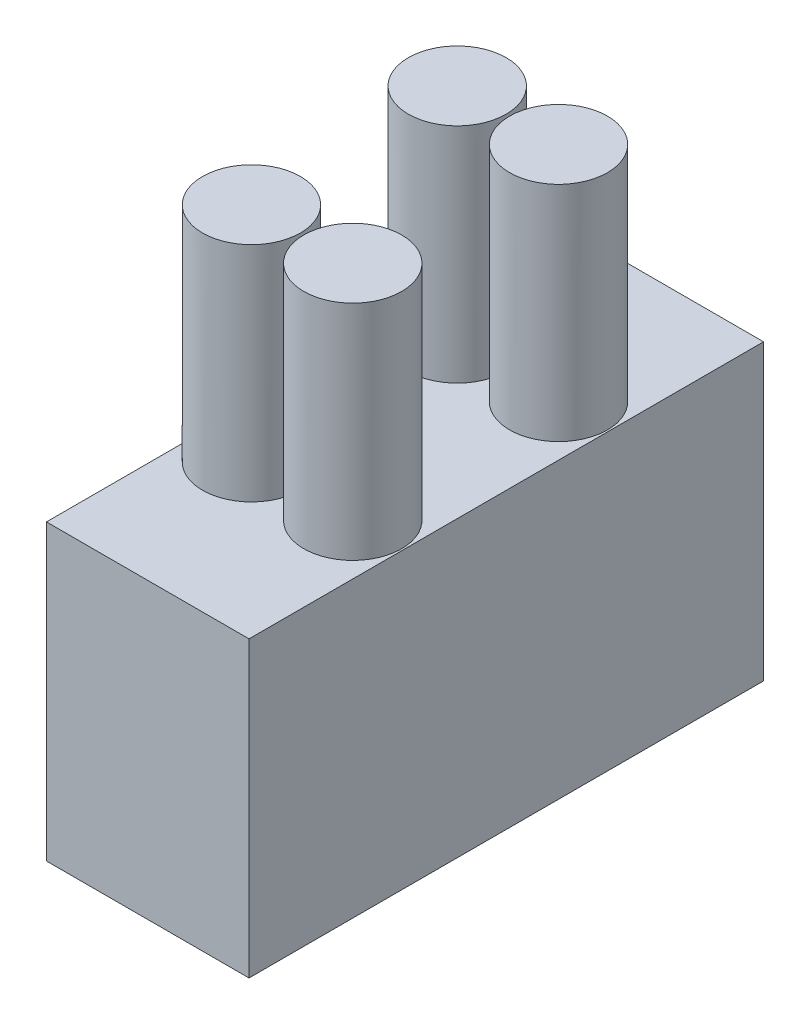
SolidWorks part; units mm, degrees
ref_plane "Front Plane" through (0, 0, 0) normal (0, 0, 1) x (1, 0, 0)
ref_plane "Top Plane" through (0, 0, 0) normal (0, 1, 0) x (1, 0, 0)
ref_plane "Right Plane" through (0, 0, 0) normal (1, 0, 0) x (0, 0, -1)
sketch "Sketch1" plane through (0, 0, 0) normal (0, 1, 0) x (1, 0, 0)
  line L1 (0, 0) -> (6, 0)
  line L2 (0, 0) -> (0, 15.24)
  line L3 (0, 15.24) -> (6, 15.24)
  line L4 (6, 0) -> (6, 15.24)
  dimension "D1" = 6
  dimension "D2" = 15.24
extrude "Boss-Extrude1" add sketch "Sketch1" along normal blind 8.7
sketch "Sketch2" plane through (0, 8.7, 0) normal (0, 1, 0) x (1, 0, 0)
  line L0 (0, 15.24) -> (0, 0) construction
  line L1 (1.5, 10.668) -> (4.5, 10.668) construction
  line L2 (1.5, 10.668) -> (1.5, 4.572) construction
  line L3 (1.5, 4.572) -> (4.5, 4.572) construction
  line L4 (4.5, 10.668) -> (4.5, 4.572) construction
  line L7 (0, 7.62) -> (1.5, 7.62) construction
  circle A0 centre (1.5, 10.668) radius 1.45
  circle A1 centre (1.5, 4.572) radius 1.45
  circle A2 centre (4.5, 4.572) radius 1.45
  circle A3 centre (4.5, 10.668) radius 1.45
  point P8 (1.7271, 5.1)
  dimension "D3" = 2.9
  dimension "D1" = 3
  dimension "D2" = 6.096
  dimension "D4" = 1.5
extrude "Boss-Extrude2" add sketch "Sketch2" along normal blind 6.6
